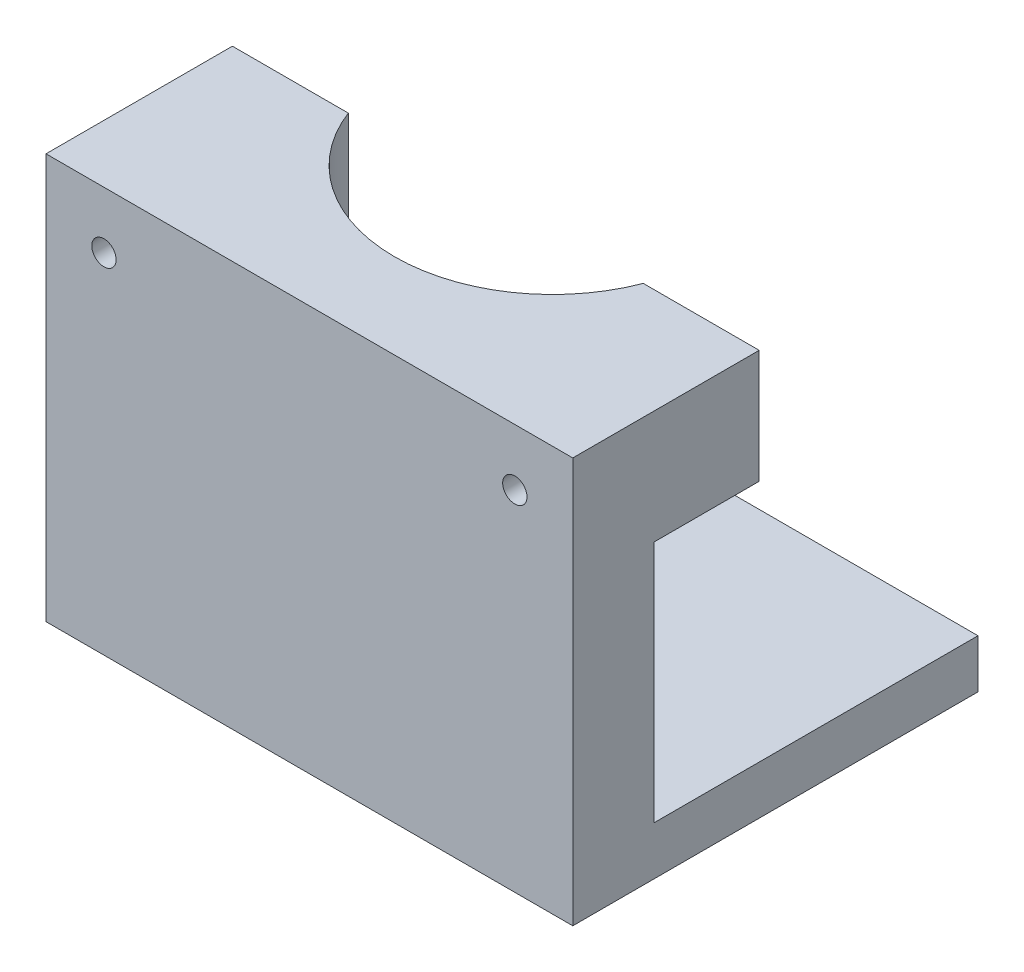
SolidWorks part; units mm, degrees
ref_plane "Front Plane" through (0, 0, 0) normal (0, 0, 1) x (1, 0, 0)
ref_plane "Top Plane" through (0, 0, 0) normal (0, 1, 0) x (1, 0, 0)
ref_plane "Right Plane" through (0, 0, 0) normal (1, 0, 0) x (0, 0, -1)
sketch "Sketch1" plane through (0, 0, 0) normal (0, 1, 0) x (1, 0, 0)
  line L1 (0, 50) -> (65, 50)
  line L2 (0, 50) -> (0, 0)
  line L3 (0, 0) -> (65, 0)
  line L4 (65, 50) -> (65, 0)
  dimension "D1" = 65
  dimension "D2" = 50
extrude "Boss-Extrude1" add sketch "Sketch1" along normal blind 6
sketch "Sketch2" plane through (0, 6, 0) normal (0, 1, 0) x (1, 0, 0)
  line L0 (65, 0) -> (65, 50) construction
  line L1 (0, 0) -> (65, 0)
  line L2 (0, 0) -> (0, 10)
  line L3 (0, 10) -> (65, 10)
  line L4 (65, 0) -> (65, 10)
  dimension "D1" = 10
extrude "Boss-Extrude2" add sketch "Sketch2" along normal blind 30
sketch "Sketch3" plane through (0, 36, 0) normal (0, 1, 0) x (1, 0, 0)
  line L0 (65, 10) -> (65, 50) construction
  line L1 (0, 0) -> (65, 0)
  line L2 (0, 0) -> (0, 23)
  line L3 (0, 23) -> (14.2997, 23)
  line L4 (65, 0) -> (65, 23)
  line L5 (0, 0) -> (65, 0) construction
  line L6 (0, 50) -> (0, 10) construction
  line L7 (50.7003, 23) -> (65, 23)
  arc A0 (14.2997, 23) -> (50.7003, 23) centre (32.5, 30) ccw
  point P13 (65, 30)
  dimension "D1" = 39
  dimension "D2" = 7
  dimension "D3" = 32.5
extrude "Boss-Extrude3" add sketch "Sketch3" along normal blind 14
sketch "Sketch4" plane through (0, 0, -23) normal (0, 0, -1) x (-1, 0, 0)
  line L0 (-65, 50) -> (-50.7003, 50) construction
  line L1 (-65, 36) -> (-50.7003, 36) construction
  line L2 (-14.2997, 36) -> (0, 36) construction
  circle A0 centre (-57.8501, 43) radius 1.5
  circle A1 centre (-7.1499, 43) radius 1.5
  point P9 (-57.8501, 36)
  point P13 (-7.1499, 36)
  dimension "D1" = 3
  dimension "D2" = 3
  dimension "D3" = 7
extrude "Cut-Extrude1" cut sketch "Sketch4" against normal up to surface (23 mm away) up to face at (32.5, 25, 0)
